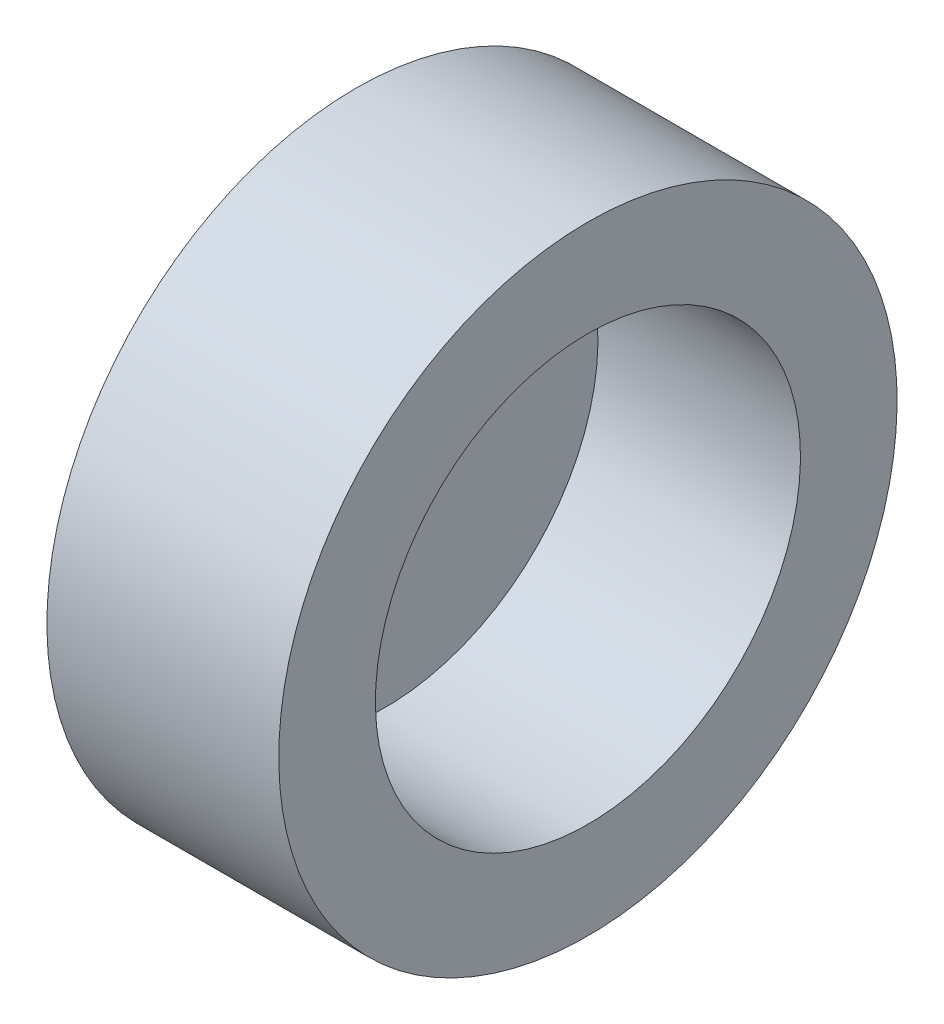
SolidWorks part; units mm, degrees
material "1.4401 (X5CrNiMo17-12-2)"
ref_plane "Plano frontal" through (0, 0, 0) normal (0, 0, 1) x (1, 0, 0)
ref_plane "Plano superior" through (0, 0, 0) normal (0, 1, 0) x (1, 0, 0)
ref_plane "Plano direito" through (0, 0, 0) normal (1, 0, 0) x (0, 0, -1)
sketch "Esboço1" plane through (0, 0, 0) normal (0, 0, 1) x (1, 0, 0)
  line L0 (0, 0.1958) -> (-120.7611, 0.1958) construction
  line L1 (-3, 5) -> (-3, 16.1958)
  line L2 (-3, 16.1958) -> (9, 16.1958)
  line L3 (9, 16.1958) -> (9, 11.1958)
  line L4 (9, 11.1958) -> (-1.481, 11.1958)
  line L5 (-1.481, 11.1958) -> (-1.481, 2)
  line L6 (-3, 5) -> (-8.481, 5)
  line L7 (-8.481, 5) -> (-8.481, 2)
  line L8 (-8.481, 2) -> (-1.481, 2)
  dimension "D1" = 12
  dimension "D2" = 3
  dimension "D3" = 5
  dimension "D4" = 16
  dimension "D7" = 7
revolve "Revolução1" add sketch "Esboço1" angle 360 about L0
